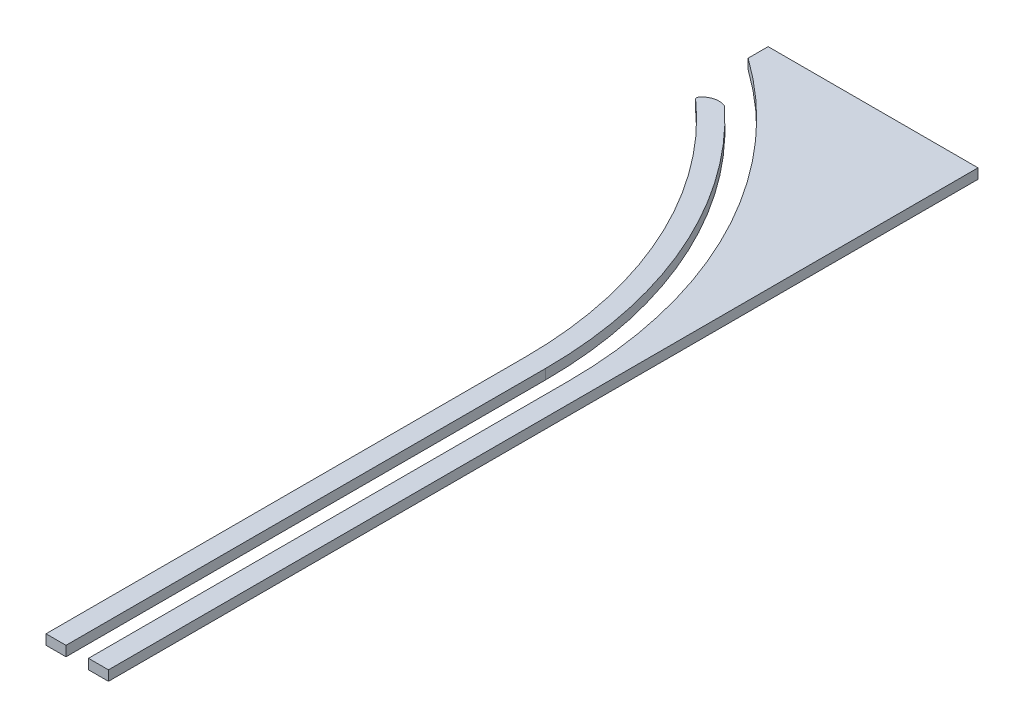
SolidWorks part; units mm, degrees
material "Pine"
ref_plane "Front Plane" through (0, 0, 0) normal (0, 0, 1) x (1, 0, 0)
ref_plane "Top Plane" through (0, 0, 0) normal (0, 1, 0) x (1, 0, 0)
ref_plane "Right Plane" through (0, 0, 0) normal (1, 0, 0) x (0, 0, -1)
sketch "Sketch2" plane through (0, 0, 0) normal (0, 1, 0) x (1, 0, 0)
  line L0 (230.1875, 0) -> (230.1875, 609.6)
  line L1 (176.2125, 0) -> (201.6125, 0)
  line L3 (-11.1125, 1104.9) -> (255.5875, 1104.9)
  line L4 (255.5875, 0) -> (255.5875, 1104.9)
  line L5 (201.6125, 0) -> (201.6125, 609.6)
  line L6 (176.2125, 0) -> (176.2125, 609.6)
  line L7 (-11.1125, 1079.5) -> (-11.1125, 1104.9)
  line L8 (230.1875, 0) -> (255.5875, 0)
  arc A0 (-11.1125, 1079.5) -> (230.1875, 609.6) centre (-347.9967, 609.6) cw
  arc A1 (26.62, 1011.76) -> (201.6125, 609.6) centre (-347.9967, 609.6) cw
  arc A2 (0.4164, 1001.2677) -> (176.2125, 609.6) centre (-347.9967, 609.6) cw
  arc A3 (-27.762, 1056.2766) -> (201.6125, 609.6) centre (-347.9967, 609.6) cw construction
  arc A4 (-42.5615, 1035.6336) -> (176.2125, 609.6) centre (-347.9967, 609.6) cw construction
  arc A6 (26.62, 1011.76) -> (0.0177, 1004.6135) centre (17.5461, 992.451) ccw
  arc A7 (0.4164, 1001.2677) -> (0.0177, 1004.6135) centre (2.1046, 1003.1655) cw
  dimension "D8" = 2.54
  dimension "D1" = 266.7
  dimension "D2" = 25.4
  dimension "D3" = 1104.9
  dimension "D4" = 609.6
  dimension "D5" = 90
  dimension "D6" = 28.575
  dimension "D9" = 25.4
  dimension "D7" = 25.4
extrude "Boss-Extrude1" add sketch "Sketch2" along normal blind 12.7
